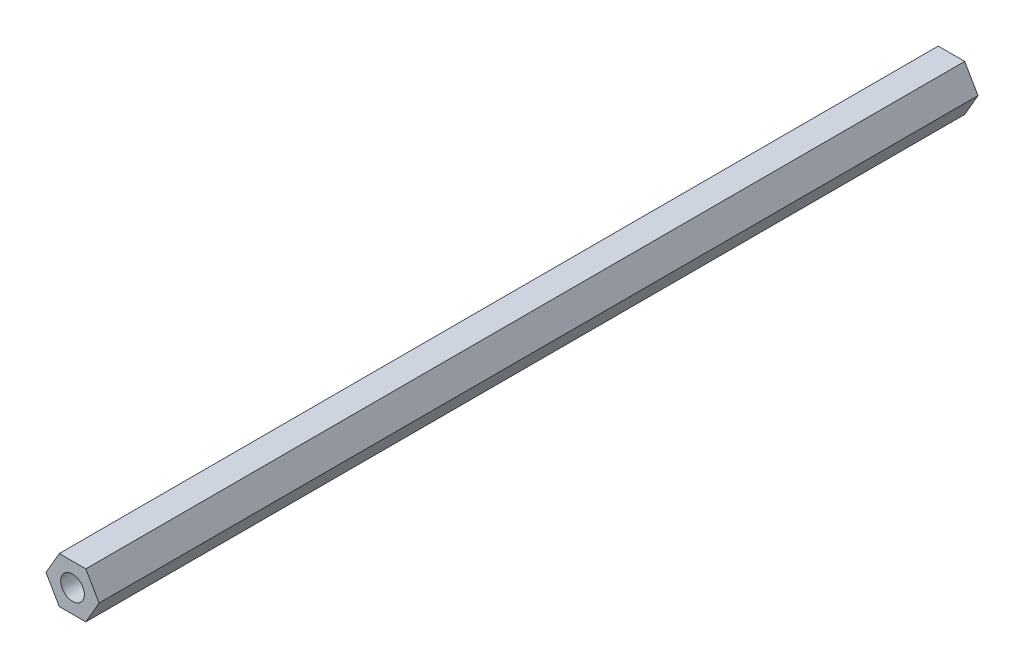
SolidWorks part; units mm, degrees
material "6061 Alloy"
ref_plane "Front Plane" through (0, 0, 0) normal (0, 0, 1) x (1, 0, 0)
ref_plane "Top Plane" through (0, 0, 0) normal (0, 1, 0) x (1, 0, 0)
ref_plane "Right Plane" through (0, 0, 0) normal (1, 0, 0) x (0, 0, -1)
sketch "Sketch1" plane through (0, 0, 0) normal (0, 0, 1) x (1, 0, 0)
  line L1 (-7.3323, 0) -> (-3.6662, -6.35)
  line L2 (-3.6662, -6.35) -> (3.6662, -6.35)
  line L3 (3.6662, -6.35) -> (7.3323, 0)
  line L4 (7.3323, 0) -> (3.6662, 6.35)
  line L5 (3.6662, 6.35) -> (-3.6662, 6.35)
  line L6 (-3.6662, 6.35) -> (-7.3323, 0)
  circle A0 centre (0, 0) radius 6.35 construction
  circle A1 centre (0, 0) radius 3.2639
  dimension "D1" = 12.7
  dimension "D2" = 6.5278
extrude "Boss-Extrude1" add sketch "Sketch1" along normal blind 242.824
